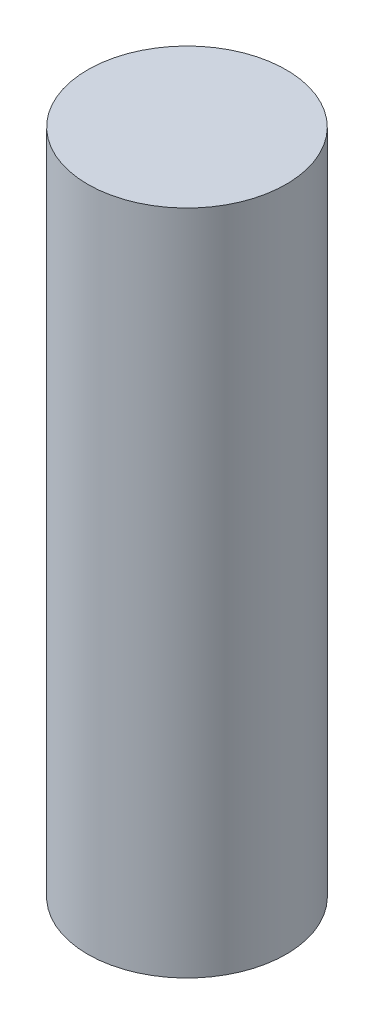
SolidWorks part; units mm, degrees
ref_plane "Front Plane" through (0, 0, 0) normal (0, 0, 1) x (1, 0, 0)
ref_plane "Top Plane" through (0, 0, 0) normal (0, 1, 0) x (1, 0, 0)
ref_plane "Right Plane" through (0, 0, 0) normal (1, 0, 0) x (0, 0, -1)
sketch "Sketch1" plane through (0, 0, 0) normal (0, 1, 0) x (1, 0, 0)
  circle A0 centre (0, 0) radius 3.5719
  dimension "D1" = 7.1437
extrude "Boss-Extrude1" add sketch "Sketch1" along normal blind 24
